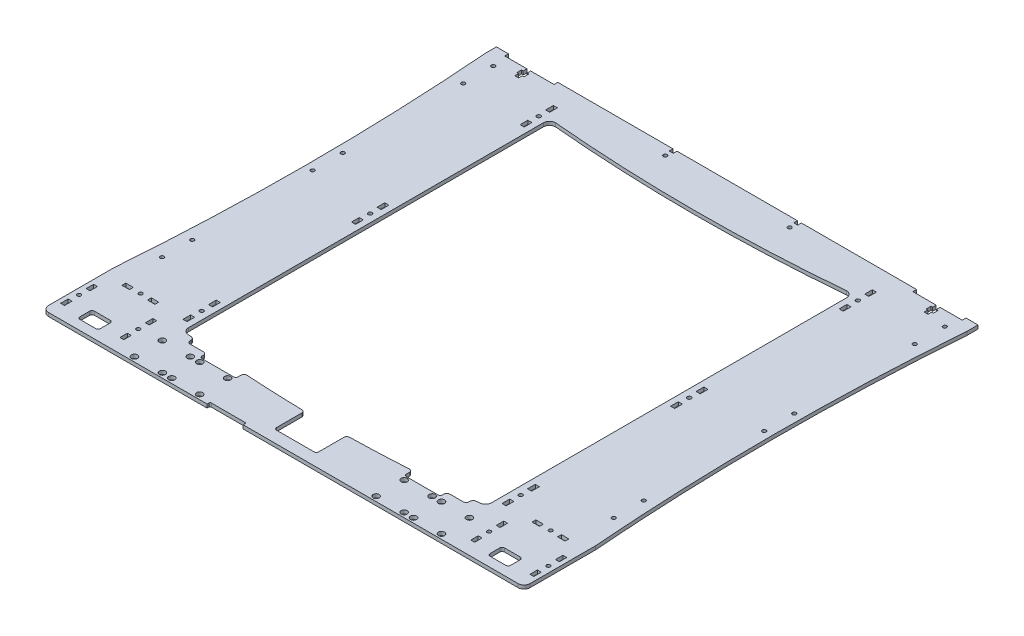
SolidWorks part; units mm, degrees
ref_plane "Alzado" through (0, 0, 0) normal (0, 0, 1) x (1, 0, 0)
ref_plane "Planta" through (0, 0, 0) normal (0, 1, 0) x (1, 0, 0)
ref_plane "Vista lateral" through (0, 0, 0) normal (1, 0, 0) x (0, 0, -1)
sketch "Croquis1" plane through (0, 0, 0) normal (0, 1, 0) x (1, 0, 0)
  line L0 (200, 377) -> (200, 0) construction
  line L1 (0, 0) -> (400, 0)
  line L2 (0, 0) -> (0, 377)
  line L3 (0, 377) -> (10, 377)
  line L4 (400, 0) -> (400, 377)
  line L5 (52.7, 17.8) -> (55.9, 17.8)
  line L6 (3.5, 17.8) -> (6.7, 17.8)
  line L7 (3.5, 17.8) -> (3.5, 11.6)
  line L8 (3.5, 11.6) -> (6.7, 11.6)
  line L9 (6.7, 17.8) -> (6.7, 11.6)
  line L10 (3.5, 39) -> (6.7, 39)
  line L11 (3.5, 39) -> (3.5, 32.8)
  line L12 (3.5, 32.8) -> (6.7, 32.8)
  line L13 (6.7, 39) -> (6.7, 32.8)
  line L14 (52.7, 17.8) -> (52.7, 11.6)
  line L15 (52.7, 11.6) -> (55.9, 11.6)
  line L16 (55.9, 17.8) -> (55.9, 11.6)
  line L17 (52.7, 39) -> (55.9, 39)
  line L18 (52.7, 39) -> (52.7, 32.8)
  line L19 (52.7, 32.8) -> (55.9, 32.8)
  line L20 (55.9, 39) -> (55.9, 32.8)
  line L21 (69.1, 218.4) -> (69.1, 212.2)
  line L22 (16, 53.2) -> (22.2, 53.2)
  line L23 (16, 53.2) -> (16, 50)
  line L24 (16, 50) -> (22.2, 50)
  line L25 (22.2, 53.2) -> (22.2, 50)
  line L26 (37.2, 53.2) -> (43.4, 53.2)
  line L27 (37.2, 53.2) -> (37.2, 50)
  line L28 (37.2, 50) -> (43.4, 50)
  line L29 (43.4, 53.2) -> (43.4, 50)
  line L30 (65.9, 57.2) -> (69.1, 57.2)
  line L31 (65.9, 57.2) -> (65.9, 51)
  line L32 (65.9, 51) -> (69.1, 51)
  line L33 (69.1, 57.2) -> (69.1, 51)
  line L34 (65.9, 78.4) -> (69.1, 78.4)
  line L35 (65.9, 78.4) -> (65.9, 72.2)
  line L36 (65.9, 72.2) -> (69.1, 72.2)
  line L37 (69.1, 78.4) -> (69.1, 72.2)
  line L38 (65.9, 218.4) -> (69.1, 218.4)
  line L39 (65.9, 218.4) -> (65.9, 212.2)
  line L40 (65.9, 212.2) -> (69.1, 212.2)
  line L41 (65.9, 197.2) -> (69.1, 197.2)
  line L42 (69.1, 197.2) -> (69.1, 191)
  line L43 (65.9, 197.2) -> (65.9, 191)
  line L44 (65.9, 191) -> (69.1, 191)
  line L45 (69.1, 78.4) -> (69.1, 218.4) construction
  line L46 (69.1, 337.2) -> (69.1, 331)
  line L47 (65.9, 337.2) -> (69.1, 337.2)
  line L48 (65.9, 337.2) -> (65.9, 331)
  line L49 (65.9, 331) -> (69.1, 331)
  line L50 (65.9, 352.2) -> (69.1, 352.2)
  line L51 (69.1, 358.4) -> (69.1, 352.2)
  line L52 (65.9, 358.4) -> (69.1, 358.4)
  line L53 (65.9, 358.4) -> (65.9, 352.2)
  line L54 (69.1, 197.2) -> (69.1, 337.2) construction
  line L55 (330.9, 197.2) -> (330.9, 337.2) construction
  line L56 (330.9, 78.4) -> (330.9, 218.4) construction
  line L57 (334.1, 358.4) -> (334.1, 352.2)
  line L58 (334.1, 358.4) -> (330.9, 358.4)
  line L59 (330.9, 358.4) -> (330.9, 352.2)
  line L60 (334.1, 352.2) -> (330.9, 352.2)
  line L61 (334.1, 331) -> (330.9, 331)
  line L62 (334.1, 337.2) -> (334.1, 331)
  line L63 (334.1, 337.2) -> (330.9, 337.2)
  line L64 (330.9, 337.2) -> (330.9, 331)
  line L65 (334.1, 191) -> (330.9, 191)
  line L66 (334.1, 197.2) -> (334.1, 191)
  line L67 (330.9, 197.2) -> (330.9, 191)
  line L68 (334.1, 197.2) -> (330.9, 197.2)
  line L69 (334.1, 212.2) -> (330.9, 212.2)
  line L70 (334.1, 218.4) -> (334.1, 212.2)
  line L71 (334.1, 218.4) -> (330.9, 218.4)
  line L72 (330.9, 78.4) -> (330.9, 72.2)
  line L73 (334.1, 72.2) -> (330.9, 72.2)
  line L74 (334.1, 78.4) -> (334.1, 72.2)
  line L75 (334.1, 78.4) -> (330.9, 78.4)
  line L76 (330.9, 57.2) -> (330.9, 51)
  line L77 (334.1, 51) -> (330.9, 51)
  line L78 (334.1, 57.2) -> (334.1, 51)
  line L79 (334.1, 57.2) -> (330.9, 57.2)
  line L80 (356.6, 53.2) -> (356.6, 50)
  line L81 (362.8, 50) -> (356.6, 50)
  line L82 (362.8, 53.2) -> (362.8, 50)
  line L83 (362.8, 53.2) -> (356.6, 53.2)
  line L84 (377.8, 53.2) -> (377.8, 50)
  line L85 (384, 50) -> (377.8, 50)
  line L86 (384, 53.2) -> (384, 50)
  line L87 (384, 53.2) -> (377.8, 53.2)
  line L88 (330.9, 218.4) -> (330.9, 212.2)
  line L89 (344.1, 39) -> (344.1, 32.8)
  line L90 (347.3, 32.8) -> (344.1, 32.8)
  line L91 (347.3, 39) -> (347.3, 32.8)
  line L92 (347.3, 39) -> (344.1, 39)
  line L93 (344.1, 17.8) -> (344.1, 11.6)
  line L94 (347.3, 11.6) -> (344.1, 11.6)
  line L95 (347.3, 17.8) -> (347.3, 11.6)
  line L96 (393.3, 39) -> (393.3, 32.8)
  line L97 (396.5, 32.8) -> (393.3, 32.8)
  line L98 (396.5, 39) -> (396.5, 32.8)
  line L99 (396.5, 39) -> (393.3, 39)
  line L100 (393.3, 17.8) -> (393.3, 11.6)
  line L101 (396.5, 11.6) -> (393.3, 11.6)
  line L102 (396.5, 17.8) -> (396.5, 11.6)
  line L103 (396.5, 17.8) -> (393.3, 17.8)
  line L104 (347.3, 17.8) -> (344.1, 17.8)
  line L105 (400, 0) -> (400, 377)
  line L106 (51, 377) -> (146.7, 377)
  line L108 (10, 377) -> (10, 373.9)
  line L109 (10, 373.9) -> (28.4, 373.9)
  line L110 (51, 377) -> (51, 373.9)
  line L111 (31.6, 373.9) -> (51, 373.9)
  line L113 (28.4, 373.9) -> (28.4, 370.9)
  line L114 (28.4, 363.9) -> (31.6, 363.9)
  line L115 (31.6, 373.9) -> (31.6, 370.9)
  line L116 (27, 370.9) -> (28.4, 370.9)
  line L117 (27, 370.9) -> (27, 366.9)
  line L118 (27, 366.9) -> (28.4, 366.9)
  line L119 (33, 370.9) -> (33, 366.9)
  line L120 (31.6, 370.9) -> (33, 370.9)
  line L121 (31.6, 366.9) -> (31.6, 363.9)
  line L122 (28.4, 366.9) -> (28.4, 363.9)
  line L123 (31.6, 366.9) -> (33, 366.9)
  line L124 (349, 377) -> (349, 373.9)
  line L125 (368.4, 373.9) -> (349, 373.9)
  line L126 (368.4, 373.9) -> (368.4, 370.9)
  line L127 (368.4, 370.9) -> (367, 370.9)
  line L128 (367, 370.9) -> (367, 366.9)
  line L129 (368.4, 366.9) -> (367, 366.9)
  line L130 (368.4, 366.9) -> (368.4, 363.9)
  line L131 (371.6, 363.9) -> (368.4, 363.9)
  line L132 (371.6, 366.9) -> (371.6, 363.9)
  line L133 (373, 366.9) -> (371.6, 366.9)
  line L134 (373, 370.9) -> (373, 366.9)
  line L135 (373, 370.9) -> (371.6, 370.9)
  line L136 (371.6, 373.9) -> (371.6, 370.9)
  line L137 (390, 373.9) -> (371.6, 373.9)
  line L138 (390, 377) -> (390, 373.9)
  line L139 (390, 377) -> (400, 377)
  line L140 (69.1, 51) -> (69.1, 0) construction
  line L141 (99.1, 31) -> (69.1, 0) construction
  line L142 (69.1, 0) -> (99.1, 0)
  line L143 (69.1, 0) -> (69.1, 31) construction
  line L144 (69.1, 31) -> (99.1, 31) construction
  line L145 (99.1, 0) -> (99.1, 31) construction
  line L146 (99.6, 0) -> (99.6, 37.4867) construction
  line L147 (72.5, 3.9) -> (95.7, 3.9) construction
  line L148 (72.5, 3.9) -> (72.5, 27.1) construction
  line L149 (72.5, 27.1) -> (95.7, 27.1) construction
  line L150 (95.7, 3.9) -> (95.7, 27.1) construction
  line L151 (72.5, 3.9) -> (95.7, 27.1) construction
  line L152 (72.5, 27.1) -> (95.7, 3.9) construction
  line L153 (150, 377) -> (250, 377)
  line L155 (146.7, 377) -> (146.7, 373.9)
  line L156 (146.7, 373.9) -> (150, 373.9)
  line L157 (150, 377) -> (150, 373.9)
  line L158 (148.35, 373.9) -> (148.35, 357.7293) construction
  line L159 (253.3, 377) -> (253.3, 373.9)
  line L160 (253.3, 373.9) -> (250, 373.9)
  line L161 (250, 377) -> (250, 373.9)
  line L162 (253.3, 377) -> (349, 377)
  line L163 (12.5, 366.9) -> (12.5, 0) construction
  circle A0 centre (5.1, 25.3) radius 1.55
  circle A1 centre (54.3, 25.3) radius 1.55
  circle A2 centre (67.5, 64.7) radius 1.6
  circle A3 centre (67.5, 204.7) radius 1.6
  circle A4 centre (67.5, 344.7) radius 1.6
  circle A5 centre (332.5, 344.7) radius 1.6
  circle A6 centre (332.5, 204.7) radius 1.6
  circle A7 centre (332.5, 64.7) radius 1.6
  circle A8 centre (345.7, 25.3) radius 1.55
  circle A9 centre (394.9, 25.3) radius 1.55
  circle A10 centre (29.7, 51.8) radius 1.55
  circle A11 centre (370.3, 51.8) radius 1.55
  circle A12 centre (72.5, 27.1) radius 2.55
  circle A13 centre (95.7, 27.1) radius 2.55
  circle A14 centre (72.5, 3.9) radius 2.55
  circle A15 centre (95.7, 3.9) radius 2.55
  circle A16 centre (327.5, 27.1) radius 2.55
  circle A17 centre (327.5, 3.9) radius 2.55
  circle A18 centre (304.3, 3.9) radius 2.55
  circle A19 centre (304.3, 27.1) radius 2.55
  circle A28 centre (103.5, 3.9) radius 2.55
  circle A29 centre (126.7, 3.9) radius 2.55
  circle A30 centre (126.7, 27.1) radius 2.55
  circle A31 centre (103.5, 27.1) radius 2.55
  circle A32 centre (273.3, 3.9) radius 2.55
  circle A33 centre (296.5, 3.9) radius 2.55
  circle A34 centre (296.5, 27.1) radius 2.55
  circle A35 centre (273.3, 27.1) radius 2.55
  circle A36 centre (148.35, 368.9) radius 1.55
  circle A37 centre (251.65, 368.9) radius 1.55
  circle A38 centre (12.5, 361.9) radius 1.55
  circle A39 centre (12.5, 336.9) radius 1.55
  circle A40 centre (12.5, 311.9) radius 1.55 [skipped]
  circle A41 centre (12.5, 286.9) radius 1.55 [skipped]
  circle A42 centre (12.5, 261.9) radius 1.55 [skipped]
  circle A43 centre (12.5, 236.9) radius 1.55
  circle A44 centre (12.5, 211.9) radius 1.55
  circle A45 centre (12.5, 186.9) radius 1.55 [skipped]
  circle A46 centre (12.5, 161.9) radius 1.55 [skipped]
  circle A48 centre (12.5, 111.9) radius 1.55
  circle A49 centre (12.5, 86.9) radius 1.55
  circle A50 centre (12.5, 136.9) radius 1.55 [skipped]
  circle A51 centre (387.5, 86.9) radius 1.55
  circle A52 centre (387.5, 111.9) radius 1.55
  circle A53 centre (387.5, 211.9) radius 1.55
  circle A54 centre (387.5, 236.9) radius 1.55
  circle A55 centre (387.5, 336.9) radius 1.55
  circle A56 centre (387.5, 361.9) radius 1.55
  point P43 (69.1, 54.1)
  point P168 (84.1, 15.5)
  point P219 (12.5, 73.9)
  dimension "D11" = 3.1
  dimension "D14" = 2
  dimension "D32" = 3.2
  dimension "D34" = 67.5
  dimension "D39" = 3.1
  dimension "D40" = 7.5
  dimension "D56" = 5.1
  dimension "D57" = 0.5
  dimension "D58" = 3.3
  dimension "D61" = 3.1
  dimension "D62" = 5
  dimension "D63" = 12.5
  dimension "D64" = 3.1
  dimension "D68" = 25
  dimension "D1" = 377
  dimension "D2" = 400
  dimension "D3" = 3.2
  dimension "D4" = 6.2
  dimension "D5" = 6.2
  dimension "D6" = 3.2
  dimension "D7" = 3.5
  dimension "D8" = 11.6
  dimension "D9" = 15
  dimension "D10" = 3.5
  dimension "D12" = 7.5
  dimension "D13" = 5.1
  dimension "D15" = 46
  dimension "D16" = 6.2
  dimension "D17" = 6.2
  dimension "D18" = 3.2
  dimension "D19" = 3.2
  dimension "D20" = 15
  dimension "D21" = 16
  dimension "D22" = 50
  dimension "D23" = 50
  dimension "D24" = 3.2
  dimension "D25" = 6.2
  dimension "D26" = 6.2
  dimension "D27" = 3.2
  dimension "D28" = 65.9
  dimension "D29" = 65.9
  dimension "D30" = 15
  dimension "D31" = 51
  dimension "D33" = 7.5
  dimension "D36" = 140
  dimension "D38" = 140
  dimension "D41" = 1.4
  dimension "D42" = 3.1
  dimension "D43" = 10
  dimension "D44" = 41
  dimension "D45" = 3.2
  dimension "D46" = 10
  dimension "D47" = 4
  dimension "D48" = 6
  dimension "D49" = 1.4
  dimension "D50" = 3
  dimension "D51" = 18.4
  dimension "D52" = 30
  dimension "D53" = 31
  dimension "D54" = 23.2
  dimension "D55" = 23.2
  dimension "D59" = 3.1
  dimension "D60" = 50
  dimension "D65" = 12
  dimension "D66" = 300
  dimension "D35" = 2
  dimension "D37" = 2
  dimension "D67" = 12
extrude "Saliente-Extruir1" add sketch "Croquis1" along normal blind 3 contours L1 L4 L3 L2 A8 A6 L57 L60 L59 L58 L34 L37 L36 L35 L30 L33 L32 L31 L26 L29 L28 L27 L22 L25 L24 L23 L17 L20 L19 L18 L5 L16 L15 L14 L10 L13 L12 L11 L6 L9
sketch "Croquis2" plane through (0, 3, 0) normal (0, 1, 0) x (1, 0, 0)
  line L0 (51, 377) -> (146.7, 377) construction
  line L1 (79.1, 347) -> (320.9, 347) construction
  line L2 (74.1, 342) -> (74.1, 47.1)
  line L3 (79.1, 42.1) -> (320.9, 42.1) construction
  line L4 (325.9, 342) -> (325.9, 47.1)
  line L5 (69.1, 337.2) -> (69.1, 331) construction
  line L6 (330.9, 337.2) -> (330.9, 331) construction
  circle A0 centre (273.3, 27.1) radius 2.55 construction
  arc A1 (325.9, 47.1) -> (320.9, 42.1) centre (320.9, 47.1) cw
  arc A2 (79.1, 347) -> (320.9, 347) centre (200, 1692.3457) ccw
  arc A3 (74.1, 342) -> (79.1, 347) centre (79.1, 342) cw
  arc A4 (320.9, 347) -> (325.9, 342) centre (320.9, 342) cw
  arc A5 (79.1, 42.1) -> (74.1, 47.1) centre (79.1, 47.1) cw
  arc A6 (79.1, 42.1) -> (320.9, 42.1) centre (200, 1082.7326) ccw
  dimension "D5" = 5
  dimension "D6" = 5
  dimension "D1" = 30
  dimension "D2" = 5
  dimension "D3" = 5
  dimension "D4" = 15
extrude "Cortar-Extruir1" cut sketch "Croquis2" against normal up to surface (3 mm away) up to face at (387.5, 0, -335.35)
fillet "Redondeo1" radius 5 2 edges at (400, 1.5, 0) (0, 1.5, 0)
sketch "Croquis4" plane through (0, 3, 0) normal (0, 1, 0) x (1, 0, 0)
  line L0 (0, 5) -> (0, 377) construction
  line L1 (0, 368) -> (6, 368) construction
  line L2 (0, 368) -> (0, 59.2)
  line L3 (0, 59.2) -> (6, 59.2) construction
  line L4 (6, 368) -> (6, 59.2) construction
  line L6 (10, 373.9) -> (28.4, 373.9) construction
  line L7 (200, 377) -> (200, 0) construction
  line L9 (150, 377) -> (250, 377) construction
  line L12 (5, 0) -> (395, 0) construction
  line L13 (400, 368) -> (400, 59.2)
  arc A0 (0, 368) -> (0, 59.2) centre (-1983.6133, 213.6) cw
  arc A2 (0, 368) -> (0, 59.2) centre (1983.6133, 213.6) ccw
  arc A3 (400, 368) -> (400, 59.2) centre (2383.6133, 213.6) ccw
  circle A4 centre (29.7, 51.8) radius 1.55 construction
  dimension "D2" = 7.4
  dimension "D1" = 5.9
  dimension "D3" = 6
extrude "Cortar-Extruir3" cut sketch "Croquis4" against normal up to surface (3 mm away) contours A0 L2 | L13 A3 up to face at (200, 0, -192.9974)
sketch "Croquis5" plane through (0, 3, 0) normal (0, 1, 0) x (1, 0, 0)
  line L0 (100.1, 29.335) -> (100.1, 41.5) construction
  line L5 (130.1, 28.5) -> (130.1, 47.9346) construction
  line L7 (200, 0) -> (200, 92.2455) construction
  line L8 (100.1, 30.5) -> (130.1, 30.5)
  line L9 (100.1, 30.5) -> (100.1, 41.5)
  line L10 (100.1, 41.5) -> (130.1, 41.5)
  line L11 (130.1, 30.5) -> (130.1, 41.5)
  line L12 (5, 0) -> (395, 0) construction
  line L13 (299.9, 30.5) -> (299.9, 41.5)
  line L14 (299.9, 30.5) -> (269.9, 30.5)
  line L15 (299.9, 41.5) -> (269.9, 41.5)
  line L16 (269.9, 30.5) -> (269.9, 41.5)
  line L17 (6.7, 17.8) -> (6.7, 11.6) construction
  line L18 (182.5, 35.2467) -> (217.5, 35.2467)
  line L19 (182.5, 35.2467) -> (182.5, 10)
  line L20 (182.5, 10) -> (217.5, 10)
  line L21 (217.5, 35.2467) -> (217.5, 10)
  line L22 (23.2, 20) -> (36.2, 20)
  line L23 (21.2, 18) -> (21.2, 10)
  line L24 (23.2, 8) -> (36.2, 8)
  line L25 (38.2, 18) -> (38.2, 10)
  line L27 (378.8, 18) -> (378.8, 10)
  line L28 (376.8, 8) -> (363.8, 8)
  line L29 (361.8, 18) -> (361.8, 10)
  line L30 (376.8, 20) -> (363.8, 20)
  arc A0 (79.1, 42.1) -> (320.9, 42.1) centre (200, 1082.7326) ccw construction
  arc A1 (23.2, 20) -> (21.2, 18) centre (23.2, 18) ccw
  arc A2 (38.2, 18) -> (36.2, 20) centre (36.2, 18) ccw
  arc A3 (36.2, 8) -> (38.2, 10) centre (36.2, 10) ccw
  arc A4 (23.2, 8) -> (21.2, 10) centre (23.2, 10) cw
  arc A5 (376.8, 20) -> (378.8, 18) centre (376.8, 18) cw
  arc A6 (376.8, 8) -> (378.8, 10) centre (376.8, 10) ccw
  arc A7 (363.8, 8) -> (361.8, 10) centre (363.8, 10) cw
  arc A8 (361.8, 18) -> (363.8, 20) centre (363.8, 18) cw
  circle A9 centre (103.5, 27.1) radius 2.55 construction
  point P36 (21.2, 20)
  point P37 (38.2, 20)
  point P40 (38.2, 8)
  dimension "D9" = 2
  dimension "D1" = 11
  dimension "D2" = 10
  dimension "D3" = 35
  dimension "D4" = 17.5
  dimension "D5" = 17
  dimension "D6" = 12
  dimension "D7" = 8
  dimension "D8" = 14.5
  dimension "D10" = 3.4
  dimension "D11" = 3.4
  dimension "D12" = 2.235
extrude "Cortar-Extruir4" cut sketch "Croquis5" against normal up to surface (3 mm away) up to face at (387.5, 0, -360.35)
fillet "Redondeo2" radius 2 6 edges at (299.9, 1.5, -30.5) (269.9, 1.5, -30.5) (100.1, 1.5, -30.5) (130.1, 1.5, -30.5) (217.5, 1.5, -10) (182.5, 1.5, -10)
sketch "Croquis6" plane through (0, 3, 0) normal (0, 1, 0) x (1, 0, 0)
  line L0 (5, 0) -> (395, 0) construction
  line L1 (136.7, 0) -> (166.7, 0)
  line L2 (136.7, 0) -> (136.7, 1.5)
  line L3 (137.7, 2.5) -> (165.7, 2.5)
  line L4 (166.7, 0) -> (166.7, 1.5)
  circle A0 centre (126.7, 3.9) radius 2.55 construction
  arc A1 (136.7, 1.5) -> (137.7, 2.5) centre (137.7, 1.5) cw
  arc A2 (165.7, 2.5) -> (166.7, 1.5) centre (165.7, 1.5) cw
  point P10 (136.7, 2.5)
  point P13 (166.7, 2.5)
  dimension "D4" = 1
  dimension "D1" = 30
  dimension "D2" = 2.5
  dimension "D3" = 10
extrude "Cortar-Extruir5" cut sketch "Croquis6" against normal up to surface (3 mm away) up to face at (200, 0, -79.5709)
sketch "Croquis7" plane through (0, 3, 0) normal (0, 1, 0) x (1, 0, 0)
  line L0 (200, 377) -> (200, 0) construction
  line L1 (150, 377) -> (250, 377) construction
  line L2 (166.7, 0) -> (395, 0) construction
  line L3 (100.1, 39.8745) -> (100.1, 32.5) construction
  line L4 (100.1, 36.0313) -> (84.1, 36.0313)
  line L5 (100.1, 36.0313) -> (100.1, 41.5313)
  line L6 (100.1, 41.5313) -> (84.1, 41.5313)
  line L7 (84.1, 36.0313) -> (84.1, 41.5313)
  line L8 (299.9, 41.5313) -> (315.9, 41.5313)
  line L9 (315.9, 36.0313) -> (315.9, 41.5313)
  line L10 (299.9, 36.0313) -> (299.9, 41.5313)
  line L11 (299.9, 36.0313) -> (315.9, 36.0313)
  arc A1 (79.1, 42.1) -> (100.1, 39.8745) centre (200, 1082.7326) ccw construction
  dimension "D1" = 5.5
  dimension "D3" = 16
extrude "Cortar-Extruir6" cut sketch "Croquis7" against normal up to surface (3 mm away) up to face at (200, 0, -79.5709)
fillet "Redondeo3" radius 2.5 10 edges at (269.9, 1.5, -37.435) (315.9, 1.5, -41.5313) (299.9, 1.5, -36.0313) (217.5, 1.5, -35.2467) (182.5, 1.5, -35.2467) (130.1, 1.5, -37.435) (100.1, 1.5, -36.0313) (84.1, 1.5, -41.5313) (315.9, 1.5, -36.0313) (84.1, 1.5, -36.0313)
sketch "Croquis8" plane through (0, 3, 0) normal (0, 1, 0) x (1, 0, 0)
  line L4 (65.9, 358.4) -> (69.1, 358.4) construction
  line L5 (65.9, 358.4) -> (69.1, 358.4)
  line L6 (65.9, 358.4) -> (65.9, 352.2) construction
  line L7 (65.9, 352.2) -> (69.1, 352.2) construction
  line L8 (69.2, 352.1) -> (69.2, 358.5)
  line L9 (69.2, 358.5) -> (65.8, 358.5)
  line L10 (65.8, 358.5) -> (65.8, 352.1)
  line L11 (65.8, 352.1) -> (69.2, 352.1)
  line L12 (69.2, 352.1) -> (69.2, 358.5)
  line L13 (69.2, 358.5) -> (65.8, 358.5)
  line L14 (65.8, 358.5) -> (65.8, 352.1)
  line L15 (65.8, 352.1) -> (69.2, 352.1)
  line L16 (69.1, 358.4) -> (69.1, 352.2) construction
  line L17 (65.9, 358.4) -> (65.9, 352.2)
  line L18 (65.9, 352.2) -> (69.1, 352.2)
  line L19 (69.1, 358.4) -> (69.1, 352.2)
  line L20 (65.9, 331) -> (69.1, 331) construction
  line L21 (65.9, 337.2) -> (65.9, 331) construction
  line L22 (69.1, 337.2) -> (69.1, 331) construction
  line L23 (65.9, 337.2) -> (69.1, 337.2) construction
  line L24 (65.9, 331) -> (69.1, 331)
  line L25 (65.9, 337.2) -> (65.9, 331)
  line L26 (69.1, 337.2) -> (69.1, 331)
  line L27 (65.9, 337.2) -> (69.1, 337.2)
  line L28 (65.8, 337.3) -> (69.2, 337.3)
  line L29 (69.2, 337.3) -> (69.2, 330.9)
  line L30 (65.8, 330.9) -> (69.2, 330.9)
  line L31 (65.8, 337.3) -> (65.8, 330.9)
  line L32 (65.9, 218.4) -> (69.1, 218.4) construction
  line L33 (65.9, 218.4) -> (65.9, 212.2) construction
  line L34 (69.1, 218.4) -> (69.1, 212.2) construction
  line L35 (65.9, 212.2) -> (69.1, 212.2) construction
  line L36 (65.9, 218.4) -> (69.1, 218.4)
  line L37 (65.9, 218.4) -> (65.9, 212.2)
  line L38 (69.1, 218.4) -> (69.1, 212.2)
  line L39 (65.9, 212.2) -> (69.1, 212.2)
  line L40 (65.8, 218.5) -> (69.2, 218.5)
  line L41 (69.2, 218.5) -> (69.2, 212.1)
  line L42 (65.8, 212.1) -> (69.2, 212.1)
  line L43 (65.8, 218.5) -> (65.8, 212.1)
  line L44 (65.9, 191) -> (69.1, 191) construction
  line L45 (65.9, 197.2) -> (65.9, 191) construction
  line L46 (69.1, 197.2) -> (69.1, 191) construction
  line L47 (65.9, 197.2) -> (69.1, 197.2) construction
  line L48 (65.9, 191) -> (69.1, 191)
  line L49 (65.9, 197.2) -> (65.9, 191)
  line L50 (69.1, 197.2) -> (69.1, 191)
  line L51 (65.9, 197.2) -> (69.1, 197.2)
  line L52 (65.8, 197.3) -> (69.2, 197.3)
  line L53 (69.2, 197.3) -> (69.2, 190.9)
  line L54 (65.8, 190.9) -> (69.2, 190.9)
  line L55 (65.8, 197.3) -> (65.8, 190.9)
  line L56 (65.9, 72.2) -> (69.1, 72.2) construction
  line L57 (65.9, 78.4) -> (65.9, 72.2) construction
  line L58 (69.1, 78.4) -> (69.1, 72.2) construction
  line L59 (65.9, 78.4) -> (69.1, 78.4) construction
  line L60 (65.9, 72.2) -> (69.1, 72.2)
  line L61 (65.9, 78.4) -> (65.9, 72.2)
  line L62 (69.1, 78.4) -> (69.1, 72.2)
  line L63 (65.9, 78.4) -> (69.1, 78.4)
  line L64 (65.8, 78.5) -> (69.2, 78.5)
  line L65 (69.2, 78.5) -> (69.2, 72.1)
  line L66 (65.8, 72.1) -> (69.2, 72.1)
  line L67 (65.8, 78.5) -> (65.8, 72.1)
  line L68 (65.9, 51) -> (69.1, 51) construction
  line L69 (65.9, 57.2) -> (65.9, 51) construction
  line L70 (69.1, 57.2) -> (69.1, 51) construction
  line L71 (65.9, 57.2) -> (69.1, 57.2) construction
  line L72 (65.9, 51) -> (69.1, 51)
  line L73 (65.9, 57.2) -> (65.9, 51)
  line L74 (69.1, 57.2) -> (69.1, 51)
  line L75 (65.9, 57.2) -> (69.1, 57.2)
  line L76 (65.8, 57.3) -> (65.8, 50.9)
  line L77 (65.8, 50.9) -> (69.2, 50.9)
  line L78 (69.2, 57.3) -> (69.2, 50.9)
  line L79 (65.8, 57.3) -> (69.2, 57.3)
  line L80 (200, 377) -> (200, 0) construction
  line L81 (150, 377) -> (250, 377) construction
  line L82 (166.7, 0) -> (395, 0) construction
  line L83 (334.2, 57.3) -> (330.8, 57.3)
  line L84 (330.8, 57.3) -> (330.8, 50.9)
  line L85 (334.2, 50.9) -> (330.8, 50.9)
  line L86 (334.2, 57.3) -> (334.2, 50.9)
  line L87 (334.1, 57.2) -> (330.9, 57.2)
  line L88 (330.9, 57.2) -> (330.9, 51)
  line L89 (334.1, 57.2) -> (334.1, 51)
  line L90 (334.1, 51) -> (330.9, 51)
  line L91 (334.2, 78.5) -> (334.2, 72.1)
  line L92 (334.2, 72.1) -> (330.8, 72.1)
  line L93 (330.8, 78.5) -> (330.8, 72.1)
  line L94 (334.2, 78.5) -> (330.8, 78.5)
  line L95 (334.1, 78.4) -> (330.9, 78.4)
  line L96 (330.9, 78.4) -> (330.9, 72.2)
  line L97 (334.1, 78.4) -> (334.1, 72.2)
  line L98 (334.1, 72.2) -> (330.9, 72.2)
  line L99 (334.2, 197.3) -> (334.2, 190.9)
  line L100 (334.2, 190.9) -> (330.8, 190.9)
  line L101 (330.8, 197.3) -> (330.8, 190.9)
  line L102 (334.2, 197.3) -> (330.8, 197.3)
  line L103 (334.1, 197.2) -> (330.9, 197.2)
  line L104 (330.9, 197.2) -> (330.9, 191)
  line L105 (334.1, 197.2) -> (334.1, 191)
  line L106 (334.1, 191) -> (330.9, 191)
  line L107 (334.2, 218.5) -> (334.2, 212.1)
  line L108 (334.2, 212.1) -> (330.8, 212.1)
  line L109 (330.8, 218.5) -> (330.8, 212.1)
  line L110 (334.2, 218.5) -> (330.8, 218.5)
  line L111 (334.1, 212.2) -> (330.9, 212.2)
  line L112 (330.9, 218.4) -> (330.9, 212.2)
  line L113 (334.1, 218.4) -> (334.1, 212.2)
  line L114 (334.1, 218.4) -> (330.9, 218.4)
  line L115 (334.2, 337.3) -> (334.2, 330.9)
  line L116 (334.2, 330.9) -> (330.8, 330.9)
  line L117 (330.8, 337.3) -> (330.8, 330.9)
  line L118 (334.2, 337.3) -> (330.8, 337.3)
  line L119 (334.1, 337.2) -> (330.9, 337.2)
  line L120 (330.9, 337.2) -> (330.9, 331)
  line L121 (334.1, 337.2) -> (334.1, 331)
  line L122 (334.1, 331) -> (330.9, 331)
  line L123 (330.9, 358.4) -> (330.9, 352.2)
  line L124 (334.1, 352.2) -> (330.9, 352.2)
  line L125 (334.1, 358.4) -> (334.1, 352.2)
  line L126 (334.2, 352.1) -> (330.8, 352.1)
  line L127 (334.2, 358.5) -> (334.2, 352.1)
  line L128 (330.8, 358.5) -> (334.2, 358.5)
  line L129 (330.8, 352.1) -> (330.8, 358.5)
  line L130 (334.1, 358.4) -> (330.9, 358.4)
  dimension "D1" = 0.1
  dimension "D2" = 0.1
  dimension "D3" = 0.1
  dimension "D4" = 0.1
  dimension "D5" = 0.1
  dimension "D6" = 0.1
extrude "Cortar-Extruir7" cut sketch "Croquis8" against normal up to surface (3 mm away)
